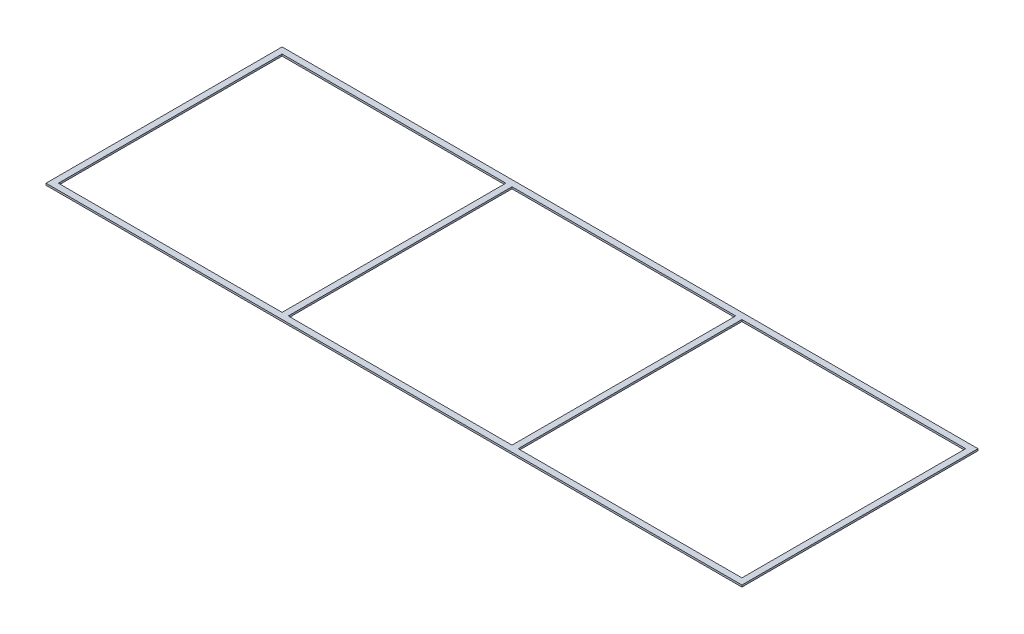
SolidWorks part; units mm, degrees
ref_plane "Front Plane" through (0, 0, 0) normal (0, 0, 1) x (1, 0, 0)
ref_plane "Top Plane" through (0, 0, 0) normal (0, 1, 0) x (1, 0, 0)
ref_plane "Right Plane" through (0, 0, 0) normal (1, 0, 0) x (0, 0, -1)
sketch "Sketch1" plane through (0, 0, 0) normal (0, 1, 0) x (1, 0, 0)
  line L5 (6.78, 2.3) -> (-6.78, 2.3)
  line L6 (6.78, 2.3) -> (6.78, -2.3)
  line L11 (6.78, -2.3) -> (-6.78, -2.3)
  line L12 (-6.78, 2.3) -> (-6.78, -2.3)
  line L17 (6.78, 2.3) -> (-6.78, -2.3) construction
  line L18 (6.78, -2.3) -> (-6.78, 2.3) construction
  point P0 (0, 0)
  dimension "D1" = 13.56
  dimension "D2" = 4.6
extrude "Base" add sketch "Sketch1" against normal blind 0.036
sketch "Sketch2" plane through (0, 0, 0) normal (0, 1, 0) x (1, 0, 0)
  line L5 (-6.78, 2.3) -> (-6.78, -2.3) construction
  line L6 (2.18, 2.18) -> (-2.18, 2.18)
  line L11 (2.18, 2.18) -> (2.18, -2.18)
  line L12 (2.18, -2.18) -> (-2.18, -2.18)
  line L17 (-2.18, 2.18) -> (-2.18, -2.18)
  line L18 (2.18, 2.18) -> (-2.18, -2.18) construction
  line L26 (2.18, -2.18) -> (-2.18, 2.18) construction
  line L27 (-2.3, 2.18) -> (-6.66, 2.18)
  line L28 (-2.3, 2.18) -> (-2.3, -2.18)
  line L29 (-2.3, -2.18) -> (-6.66, -2.18)
  line L30 (-6.66, 2.18) -> (-6.66, -2.18)
  line L31 (-2.3, 2.18) -> (-6.66, -2.18) construction
  line L32 (-2.3, -2.18) -> (-6.66, 2.18) construction
  line L33 (6.78, 2.3) -> (-6.78, 2.3) construction
  line L34 (6.78, -2.3) -> (-6.78, -2.3) construction
  line L35 (6.78, 2.3) -> (6.78, -2.3) construction
  line L36 (6.66, -2.18) -> (2.3, -2.18)
  line L37 (6.66, -2.18) -> (6.66, 2.18)
  line L38 (6.66, 2.18) -> (2.3, 2.18)
  line L39 (2.3, -2.18) -> (2.3, 2.18)
  line L40 (6.66, -2.18) -> (2.3, 2.18) construction
  line L41 (6.66, 2.18) -> (2.3, -2.18) construction
  point P0 (0, 0)
  point P6 (-4.48, 0)
  point P17 (4.48, 0)
  point P25 (0, 0)
  dimension "D1" = 0.12
  dimension "D2" = 0.12
  dimension "D3" = 0.12
  dimension "D4" = 0.12
  dimension "D5" = 4.36
  dimension "D6" = 4.36
  dimension "D7" = 0.12
  dimension "D8" = 0.12
  dimension "D9" = 4.36
extrude "Cutout Base" cut sketch "Sketch2" against normal blind 0.036
